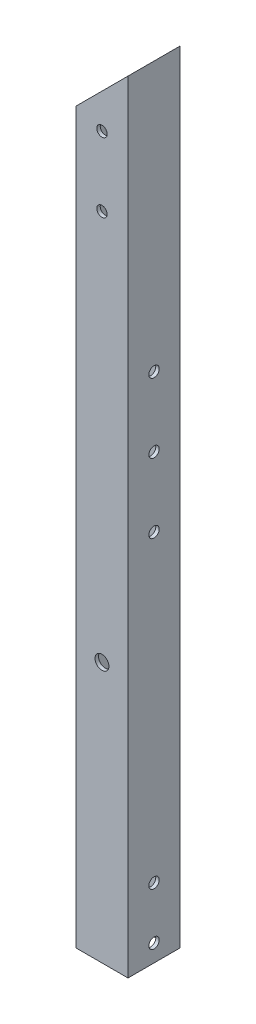
SolidWorks part; units mm, degrees
material "6061-O (SS)"
ref_plane "前视基准面" through (0, 0, 0) normal (0, 0, 1) x (1, 0, 0)
ref_plane "上视基准面" through (0, 0, 0) normal (0, 1, 0) x (1, 0, 0)
ref_plane "右视基准面" through (0, 0, 0) normal (1, 0, 0) x (0, 0, -1)
sketch "草图1" plane through (0, 0, 0) normal (0, 1, 0) x (1, 0, 0)
  line L0 (-6.5, 6.5) -> (6.5, 6.5)
  line L1 (-7.5, -7.5) -> (7.5, -7.5)
  line L2 (-7.5, -7.5) -> (-7.5, 7.5)
  line L3 (-7.5, 7.5) -> (7.5, 7.5)
  line L4 (7.5, -7.5) -> (7.5, 7.5)
  line L5 (-7.5, -7.5) -> (7.5, 7.5) construction
  line L6 (-7.5, 7.5) -> (7.5, -7.5) construction
  line L7 (6.5, -6.5) -> (6.5, 6.5)
  line L8 (-6.5, -6.5) -> (6.5, -6.5)
  line L9 (-6.5, -6.5) -> (-6.5, 6.5)
  point P0 (0, 0)
  dimension "D1" = 15
  dimension "D2" = 1
extrude "凸台-拉伸1" add sketch "草图1" along normal blind 225
sketch "草图2" plane through (0, 0, 7.5) normal (0, 0, 1) x (1, 0, 0)
  line L0 (7.5, 225) -> (-7.5, 225)
  line L1 (-7.5, 225) -> (-7.5, 210)
  line L2 (-7.5, 225) -> (-7.5, 0) construction
  line L3 (-7.5, 210) -> (7.5, 225)
  line L4 (7.5, 225) -> (7.5, 0) construction
  line L5 (0, 0) -> (0, 225) construction
  line L6 (-7.5, 0) -> (7.5, 0) construction
  circle A0 centre (0, 207.5) radius 1.5
  circle A1 centre (0, 187.5) radius 1.5
  circle A2 centre (0, 75) radius 2
  point P18 (0, 217.5)
  dimension "D1" = 75
  dimension "D2" = 4
  dimension "D3" = 10
  dimension "D4" = 20
  dimension "D5" = 3
extrude "切除-拉伸1" cut sketch "草图2" against normal through all
sketch "草图3" plane through (7.5, 0, 0) normal (1, 0, 0) x (0, 0, -1)
  line L0 (0, 225) -> (0, 0) construction
  line L1 (-7.5, 225) -> (7.5, 225) construction
  line L2 (-7.5, 0) -> (7.5, 0) construction
  circle A0 centre (0, 5) radius 1.5
  circle A1 centre (0, 20) radius 1.5
  circle A2 centre (0, 127.5) radius 1.5
  circle A3 centre (0, 147.5) radius 1.5
  circle A4 centre (0, 107.5) radius 1.5
  dimension "D1" = 5
  dimension "D2" = 15
  dimension "D3" = 3
  dimension "D5" = 20
  dimension "D6" = 20
  dimension "D4" = 97.5
extrude "切除-拉伸2" cut sketch "草图3" against normal through all
